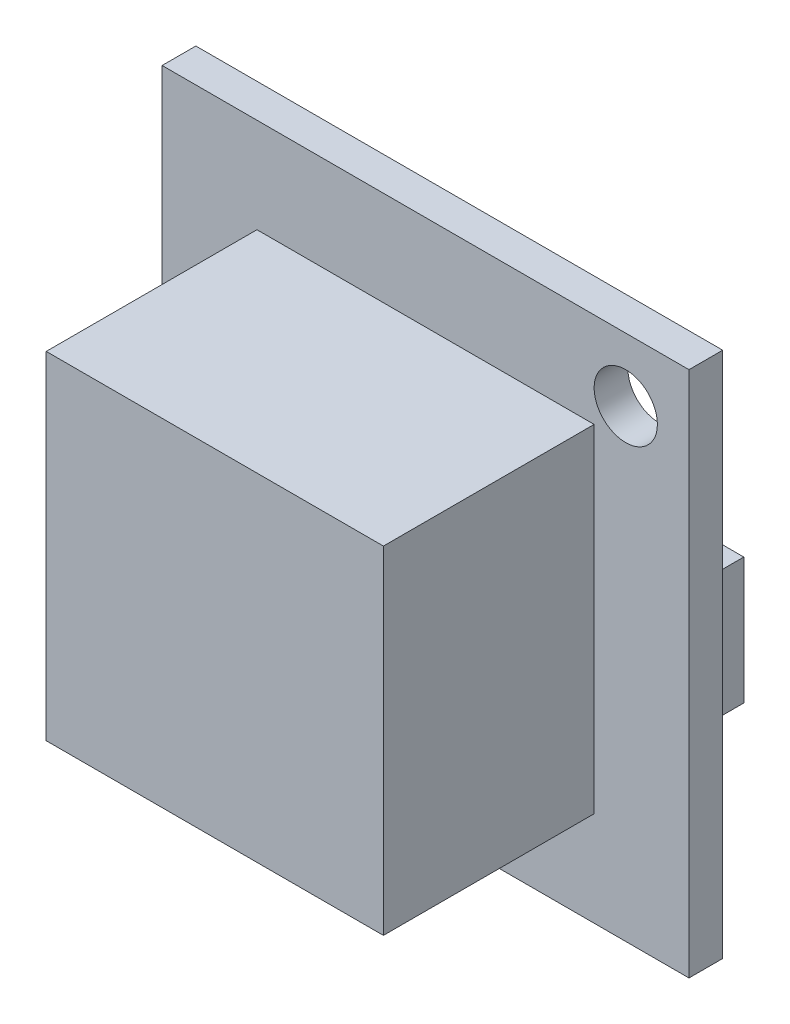
SolidWorks part; units mm, degrees
ref_plane "Front Plane" through (0, 0, 0) normal (0, 0, 1) x (1, 0, 0)
ref_plane "Top Plane" through (0, 0, 0) normal (0, 1, 0) x (1, 0, 0)
ref_plane "Right Plane" through (0, 0, 0) normal (1, 0, 0) x (0, 0, -1)
sketch "Sketch1" plane through (0, 0, 0) normal (0, 0, 1) x (1, 0, 0)
  line L1 (12.5, 12.5) -> (-12.5, 12.5)
  line L2 (12.5, 12.5) -> (12.5, -12.5)
  line L3 (12.5, -12.5) -> (-12.5, -12.5)
  line L4 (-12.5, 12.5) -> (-12.5, -12.5)
  line L5 (12.5, 12.5) -> (-12.5, -12.5) construction
  line L6 (12.5, -12.5) -> (-12.5, 12.5) construction
  point P0 (0, 0)
  dimension "D1" = 25
extrude "Boss-Extrude1" add sketch "Sketch1" along normal blind 1.6
sketch "Sketch2" plane through (0, 0, 1.6) normal (0, 0, 1) x (1, 0, 0)
  line L0 (12.5, -12.5) -> (12.5, 12.5) construction
  line L1 (12.5, 12.5) -> (-12.5, 12.5) construction
  line L2 (-12.5, -12.5) -> (12.5, -12.5) construction
  line L3 (-12.5, 12.5) -> (-12.5, -12.5) construction
  circle A0 centre (9.5, 9.5) radius 1.5
  circle A1 centre (-9.5, -9.5) radius 1.5
  dimension "D2" = 3
  dimension "D1" = 3
  dimension "D3" = 3
  dimension "D4" = 3
  dimension "D5" = 3
extrude "Cut-Extrude1" cut sketch "Sketch2" against normal through all
sketch "Sketch3" plane through (0, 0, 1.6) normal (0, 0, 1) x (1, 0, 0)
  line L1 (8, -8) -> (-8, -8)
  line L2 (8, -8) -> (8, 8)
  line L3 (8, 8) -> (-8, 8)
  line L4 (-8, -8) -> (-8, 8)
  line L5 (8, -8) -> (-8, 8) construction
  line L6 (8, 8) -> (-8, -8) construction
  point P0 (0, 0)
  dimension "D1" = 16
extrude "Boss-Extrude2" add sketch "Sketch3" along normal blind 10
sketch "Sketch4" plane through (0, 0, 0) normal (0, 0, -1) x (-1, 0, 0)
  line L0 (0, 0) -> (0, -50000) construction
  line L1 (12.5, -12.5) -> (-12.5, -12.5) construction
  line L2 (-3.5, -12.5) -> (3.5, -12.5)
  line L3 (-3.5, -12.5) -> (-3.5, -7.5)
  line L4 (-3.5, -7.5) -> (3.5, -7.5)
  line L5 (3.5, -12.5) -> (3.5, -7.5)
  dimension "D1" = 7
  dimension "D2" = 5
extrude "Boss-Extrude3" add sketch "Sketch4" along normal blind 8 separate body
sketch "Sketch5" plane through (0, 0, 0) normal (0, 0, -1) x (-1, 0, 0)
  line L0 (-12.5, 12.5) -> (12.5, 12.5) construction
  line L1 (-11.5, 2.5) -> (-5.5, 2.5)
  line L2 (-11.5, 2.5) -> (-11.5, -3.5)
  line L3 (-11.5, -3.5) -> (-5.5, -3.5)
  line L4 (-5.5, 2.5) -> (-5.5, -3.5)
  line L5 (-12.5, -12.5) -> (-12.5, 12.5) construction
  dimension "D1" = 6
  dimension "D2" = 10
  dimension "D3" = 1
extrude "Boss-Extrude4" add sketch "Sketch5" along normal blind 2
